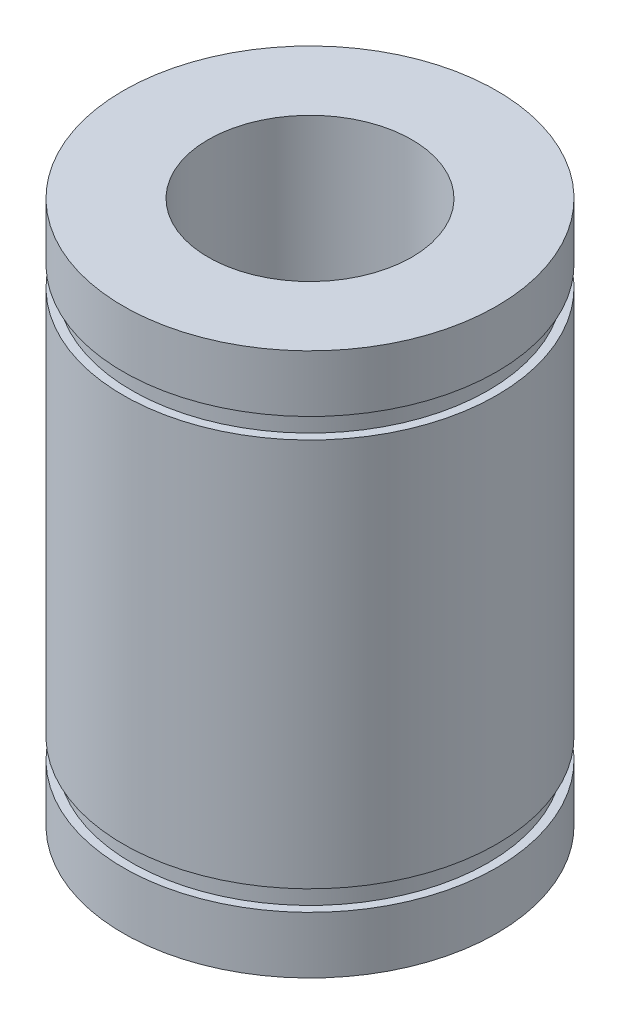
SolidWorks part; units mm, degrees
ref_plane "Front Plane" through (0, 0, 0) normal (0, 0, 1) x (1, 0, 0)
ref_plane "Top Plane" through (0, 0, 0) normal (0, 1, 0) x (1, 0, 0)
ref_plane "Right Plane" through (0, 0, 0) normal (1, 0, 0) x (0, 0, -1)
sketch "Sketch1" plane through (0, 0, 0) normal (0, 0, 1) x (1, 0, 0)
  line L0 (6, -16.4838) -> (6, 15.5162)
  line L1 (6, 15.5162) -> (11, 15.5162)
  line L2 (11, 15.5162) -> (11, 12.1662)
  line L3 (11, 12.1662) -> (10.5, 12.1662)
  line L4 (10.5, 12.1662) -> (10.5, 10.9662)
  line L5 (10.5, 10.9662) -> (11, 10.9662)
  line L6 (11, 10.9662) -> (11, -11.9338)
  line L7 (11, -11.9338) -> (10.5, -11.9338)
  line L8 (10.5, -11.9338) -> (10.5, -13.1338)
  line L9 (10.5, -13.1338) -> (11, -13.1338)
  line L10 (11, -13.1338) -> (11, -16.4838)
  line L11 (11, -16.4838) -> (6, -16.4838)
  line L12 (0, -1000) -> (0, 49000) construction
  dimension "D1" = 12
  dimension "D2" = 32
  dimension "D3" = 22.9
  dimension "D4" = 1.2
  dimension "D5" = 21
  dimension "D6" = 22
revolve "Revolve1" add sketch "Sketch1" angle 360 about L12
